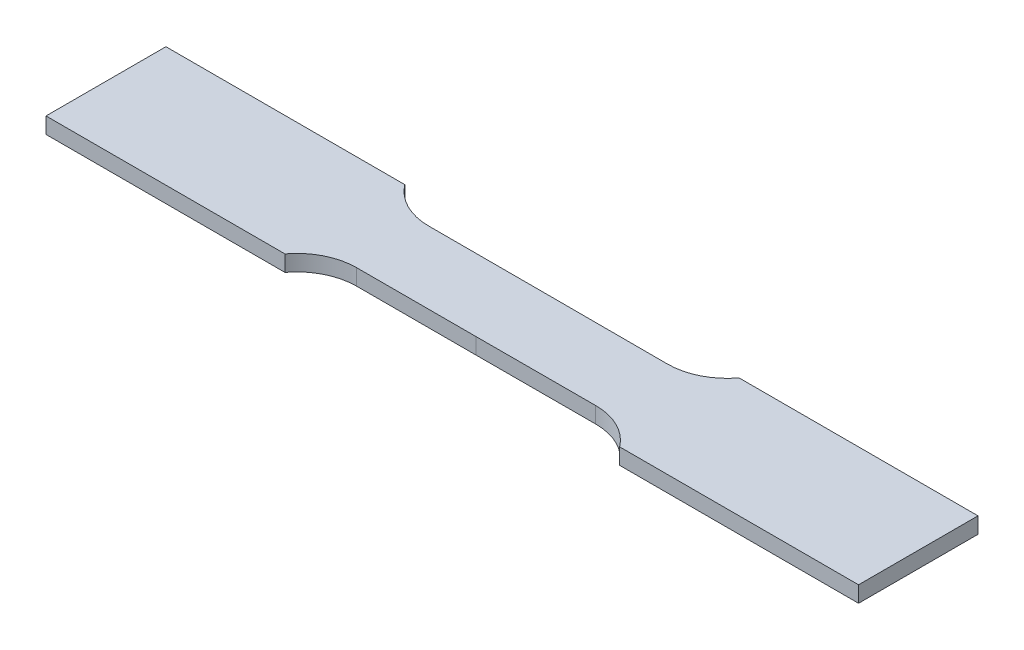
SolidWorks part; units mm, degrees
ref_plane "Front Plane" through (0, 0, 0) normal (0, 0, 1) x (1, 0, 0)
ref_plane "Top Plane" through (0, 0, 0) normal (0, 1, 0) x (1, 0, 0)
ref_plane "Right Plane" through (0, 0, 0) normal (1, 0, 0) x (0, 0, -1)
sketch "Sketch1" plane through (0, 0, 0) normal (0, 1, 0) x (1, 0, 0)
  line L3 (25, 7.515) -> (0, 7.54)
  line L4 (0, 7.54) -> (-25, 7.545)
  line L5 (-25, -7.545) -> (0, -7.54)
  line L6 (0, -7.54) -> (25, -7.515)
  line L7 (0, 7.54) -> (0, -7.54) construction
  line L8 (-25, 0) -> (25, 0) construction
  line L9 (25, 7.515) -> (25, 12.4984) construction
  line L10 (-35, 12.5483) -> (-25, 12.5483) construction
  line L11 (-25, 12.5483) -> (-25, 7.545) construction
  line L12 (-25, -12.5483) -> (-25, -7.545) construction
  line L13 (-35, 12.5483) -> (-85, 12.5483)
  line L15 (-35, -12.5483) -> (-85, -12.5483)
  line L16 (-85, 12.5483) -> (-85, -12.5483)
  line L17 (25, 12.4984) -> (35, 12.4984) construction
  line L18 (-35, -12.5483) -> (-25, -12.5483) construction
  line L19 (-25, 7.545) -> (-25, -7.545) construction
  line L20 (25, -7.515) -> (25, 7.515) construction
  line L22 (25, -7.515) -> (25, -12.4984) construction
  line L23 (25, -12.4984) -> (35, -12.4984) construction
  line L24 (35, 12.4984) -> (85, 12.4984)
  line L26 (35, -12.4984) -> (85, -12.4984)
  line L27 (85, 12.4984) -> (85, -12.4984)
  arc A0 (-35, 12.5483) -> (-25, 7.545) centre (-24.9975, 20.045) ccw
  arc A1 (-35, -12.5483) -> (-25, -7.545) centre (-24.9975, -20.045) cw
  arc A2 (35, -12.4984) -> (25, -7.515) centre (25.0125, -20.015) ccw
  arc A3 (35, 12.4984) -> (25, 7.515) centre (25.0125, 20.015) cw
  dimension "D5" = 25
  dimension "D9" = 25
  dimension "D4" = 15.08
  dimension "D6" = 10
  dimension "D8" = 50
  dimension "D1" = 15.09
  dimension "D2" = 15.03
  dimension "D3" = 50
  dimension "D10" = 10
  dimension "D11" = 50
extrude "Boss-Extrude2" add sketch "Sketch1" along normal blind 3.357 contours L24 A3 L3 L4 A0 L13 L16 L15 A1 L5 L6 A2 L26 L27
equation "\"D5@Sketch1\"=12.5*2"
equation "\"D9@Sketch1\"=12.5*2"
